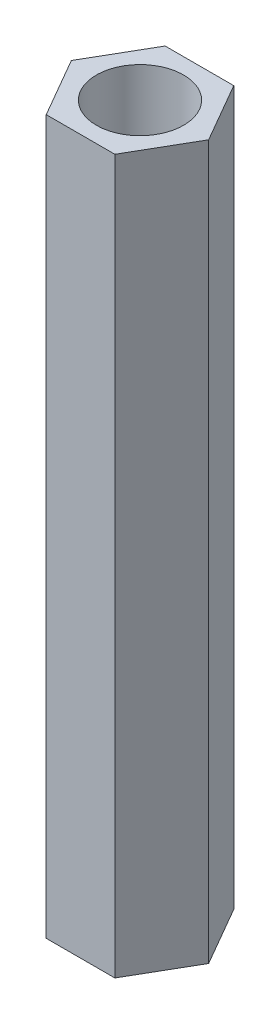
SolidWorks part; units mm, degrees
ref_plane "Front Plane" through (0, 0, 0) normal (0, 0, 1) x (1, 0, 0)
ref_plane "Top Plane" through (0, 0, 0) normal (0, 1, 0) x (1, 0, 0)
ref_plane "Right Plane" through (0, 0, 0) normal (1, 0, 0) x (0, 0, -1)
sketch "Sketch1" plane through (0, 0, 0) normal (0, 1, 0) x (1, 0, 0)
  line L0 (0, 0) -> (0, 2.0858) construction
  line L1 (0.866, -1.5) -> (1.7321, 0)
  line L2 (1.7321, 0) -> (0.866, 1.5)
  line L3 (0.866, 1.5) -> (-0.866, 1.5)
  line L4 (-0.866, 1.5) -> (-1.7321, 0)
  line L5 (-1.7321, 0) -> (-0.866, -1.5)
  line L6 (-0.866, -1.5) -> (0.866, -1.5)
  circle A0 centre (0, 0) radius 1.5 construction
  circle A1 centre (0, 0) radius 1.1
  dimension "D1" = 3
  dimension "D2" = 2.2
extrude "Boss-Extrude1" add sketch "Sketch1" along normal blind 18
